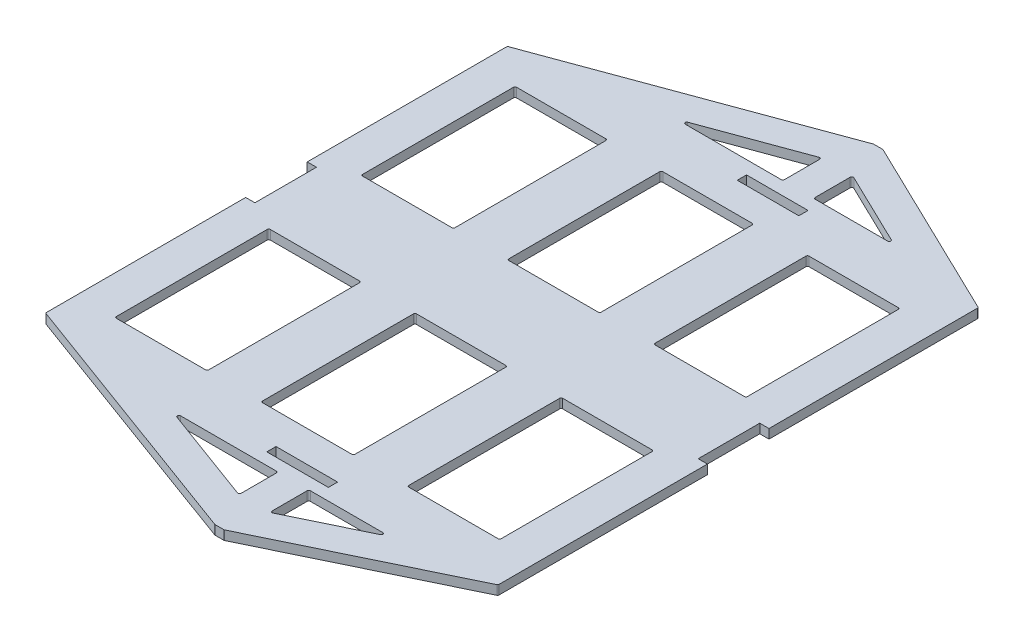
SolidWorks part; units mm, degrees
material "Beech"
ref_plane "Спереди" through (0, 0, 0) normal (0, 0, 1) x (1, 0, 0)
ref_plane "Сверху" through (0, 0, 0) normal (0, 1, 0) x (1, 0, 0)
ref_plane "Справа" through (0, 0, 0) normal (1, 0, 0) x (0, 0, -1)
sketch "Sketch1" plane through (0, 0, 0) normal (0, 1, 0) x (1, 0, 0)
  line L0 (300, 144) -> (0, 144) construction
  line L1 (300, 0) -> (300, -12)
  line L2 (300, -12) -> (180, -70)
  line L3 (180, -70) -> (174, -70)
  line L4 (174, -70) -> (0, -6)
  line L5 (0, -6) -> (0, 0)
  line L6 (300, 0) -> (300, 288)
  line L7 (180, 358) -> (174, 358)
  line L8 (0, 288) -> (0, 0)
  line L9 (0, 294) -> (0, 288)
  line L10 (174, 358) -> (0, 294)
  line L11 (300, 300) -> (180, 358)
  line L12 (300, 288) -> (300, 300)
  dimension "D1" = 300
  dimension "D2" = 6
  dimension "D3" = 12
  dimension "D4" = 6
  dimension "D5" = 120
  dimension "D6" = 58
  dimension "D7" = 288
extrude "support" add sketch "Sketch1" along normal blind 6
sketch "Sketch2" plane through (0, 6, 0) normal (0, 1, 0) x (1, 0, 0)
  line L0 (95.999, -20) -> (164.9883, -20)
  line L1 (164.9883, -20) -> (164.9883, -45.3754)
  line L2 (95.999, -20) -> (164.9883, -45.3754)
  line L3 (184.9883, -20) -> (184.9883, -45.3754)
  line L4 (184.9883, -45.3754) -> (237.4891, -20)
  line L5 (237.4891, -20) -> (184.9883, -20)
  line L7 (300, 144) -> (0, 144) construction
  line L8 (0, -6) -> (174, -70) construction
  line L9 (180, -70) -> (300, -12) construction
  line L10 (300, -12) -> (300, 300) construction
  line L11 (0, 294) -> (0, -6) construction
  line L12 (95.999, 308) -> (164.9883, 333.3754)
  line L13 (95.999, 308) -> (164.9883, 308)
  line L14 (164.9883, 308) -> (164.9883, 333.3754)
  line L15 (184.9883, 333.3754) -> (237.4891, 308)
  line L16 (184.9883, 308) -> (184.9883, 333.3754)
  line L17 (237.4891, 308) -> (184.9883, 308)
  line L18 (215, 114) -> (180, 114) construction
  line L19 (275, 14) -> (215, 14)
  line L20 (275, 14) -> (275, 114)
  line L21 (275, 114) -> (215, 114)
  line L22 (215, 14) -> (215, 114)
  line L23 (180, 14) -> (120, 14)
  line L24 (180, 14) -> (180, 114)
  line L25 (180, 114) -> (120, 114)
  line L26 (120, 14) -> (120, 114)
  line L27 (85, 14) -> (25, 14)
  line L28 (85, 14) -> (85, 114)
  line L29 (85, 114) -> (25, 114)
  line L30 (25, 14) -> (25, 114)
  line L31 (120, 114) -> (85, 114) construction
  line L32 (85, 274) -> (25, 274)
  line L33 (25, 274) -> (25, 174)
  line L34 (85, 174) -> (25, 174)
  line L35 (85, 274) -> (85, 174)
  line L36 (180, 274) -> (120, 274)
  line L37 (120, 274) -> (120, 174)
  line L38 (180, 174) -> (120, 174)
  line L39 (180, 274) -> (180, 174)
  line L40 (275, 274) -> (215, 274)
  line L41 (215, 274) -> (215, 174)
  line L42 (275, 174) -> (215, 174)
  line L43 (275, 274) -> (275, 174)
  dimension "D1" = 20
  dimension "D2" = 20
  dimension "D3" = 20
  dimension "D4" = 20
  dimension "D5" = 100
  dimension "D6" = 60
  dimension "D7" = 30
  dimension "D8" = 25
  dimension "D9" = 25
extrude "lite" cut sketch "Sketch2" against normal through all
fillet "Fillet1" radius 1 8 edges at (0, 3, -294) (174, 3, -358) (180, 3, -358) (300, 3, -300) (300, 3, 12) (180, 3, 70) (174, 3, 70) (0, 3, 6)
fillet "Fillet2" radius 1 36 edges at (237.4891, 3, 20) (184.9883, 3, 45.3754) (184.9883, 3, 20) (164.9883, 3, 45.3754) (164.9883, 3, 20) (95.999, 3, 20) (25, 3, -114) (25, 3, -14) (85, 3, -14) (85, 3, -114) (120, 3, -114) (120, 3, -14) (180, 3, -14) (180, 3, -114) (215, 3, -114) (215, 3, -14) (275, 3, -14) (275, 3, -114) (25, 3, -174) (85, 3, -174) (25, 3, -274) (85, 3, -274) (120, 3, -274) (120, 3, -174) (180, 3, -174) (180, 3, -274) (215, 3, -274) (215, 3, -174) (275, 3, -174) (275, 3, -274) (95.999, 3, -308) (164.9883, 3, -308) (164.9883, 3, -333.3754) (184.9883, 3, -308) (184.9883, 3, -333.3754) (237.4891, 3, -308)
sketch "Sketch3" plane through (0, 6, 0) normal (0, 1, 0) x (1, 0, 0)
  line L0 (0, 293.3023) -> (0, -5.3023) construction
  line L1 (0, 164) -> (6, 164)
  line L2 (0, 164) -> (0, 124)
  line L3 (0, 124) -> (6, 124)
  line L4 (6, 164) -> (6, 124)
  line L5 (300, -11.3727) -> (300, 299.3727) construction
  line L6 (300, 164) -> (294, 164)
  line L7 (300, 164) -> (300, 124)
  line L8 (300, 124) -> (294, 124)
  line L9 (294, 164) -> (294, 124)
  line L11 (190, -6.273) -> (150, -6.273)
  line L12 (190, -6.273) -> (190, -12.273)
  line L13 (190, -12.273) -> (150, -12.273)
  line L14 (150, -6.273) -> (150, -12.273)
  line L15 (190, 299.3727) -> (150, 299.3727)
  line L16 (190, 299.3727) -> (190, 293.3727)
  line L17 (190, 293.3727) -> (150, 293.3727)
  line L18 (150, 299.3727) -> (150, 293.3727)
  point P20 (300, 144)
  point P25 (294, 144)
  point P26 (6, 144)
  dimension "D1" = 6
  dimension "D2" = 40
  dimension "D3" = 110
extrude "mount" cut sketch "Sketch3" against normal through all
